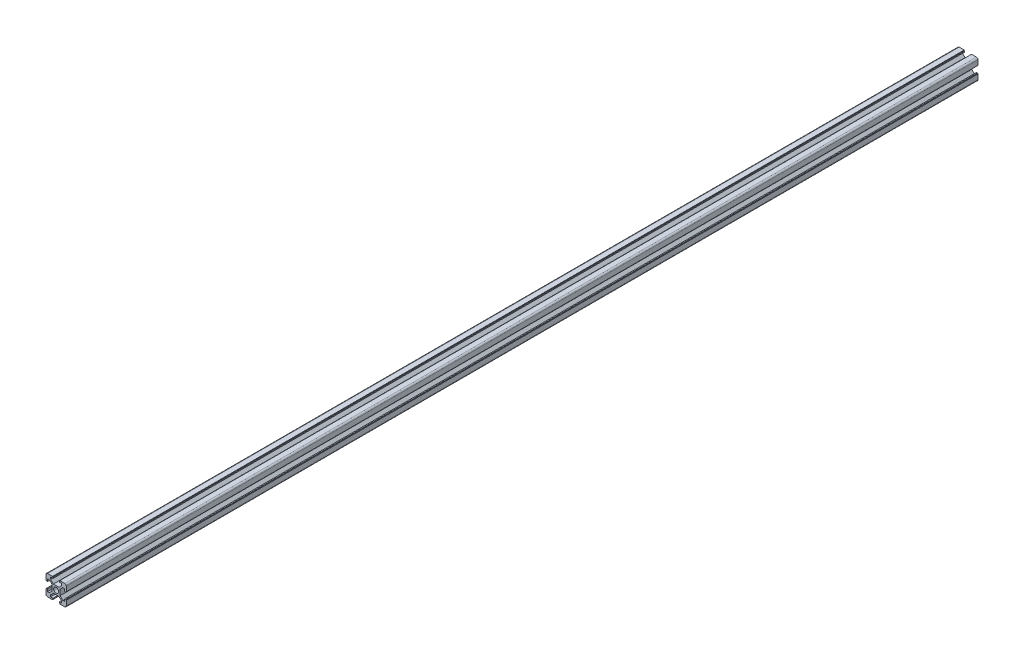
SolidWorks part; units mm, degrees
material "6061 合金"
ref_plane "前视基准面" through (0, 0, 0) normal (0, 0, 1) x (1, 0, 0)
ref_plane "上视基准面" through (0, 0, 0) normal (0, 1, 0) x (1, 0, 0)
ref_plane "右视基准面" through (0, 0, 0) normal (1, 0, 0) x (0, 0, -1)
sketch "草图1" plane through (0, 0, 0) normal (0, 0, 1) x (1, 0, 0)
  line B0 (8.5, 10) -> (3.6, 10)
  line B1 (10, 3.6) -> (10, 8.5)
  line B2 (9.5, 3.6) -> (10, 3.6)
  line B3 (9.5, 3.1) -> (9.5, 3.6)
  line B4 (8.5, 3.1) -> (9.5, 3.1)
  line B5 (8.5, 5.5) -> (8.5, 3.1)
  line B6 (6.65, 5.5) -> (8.5, 5.5)
  line B7 (3.9, 2.75) -> (6.65, 5.5)
  line B8 (3.9, -2.75) -> (3.9, 2.75)
  line B9 (6.65, -5.5) -> (3.9, -2.75)
  line B10 (8.5, -5.5) -> (6.65, -5.5)
  line B11 (8.5, -3.1) -> (8.5, -5.5)
  line B12 (9.5, -3.1) -> (8.5, -3.1)
  line B13 (9.5, -3.6) -> (9.5, -3.1)
  line B14 (10, -3.6) -> (9.5, -3.6)
  line B15 (10, -8.5) -> (10, -3.6)
  line B16 (3.6, -10) -> (8.5, -10)
  line B17 (3.6, -9.5) -> (3.6, -10)
  line B18 (3.1, -9.5) -> (3.6, -9.5)
  line B19 (3.1, -8.5) -> (3.1, -9.5)
  line B20 (5.5, -8.5) -> (3.1, -8.5)
  line B21 (5.5, -6.65) -> (5.5, -8.5)
  line B22 (2.75, -3.9) -> (5.5, -6.65)
  line B23 (-2.75, -3.9) -> (2.75, -3.9)
  line B24 (-5.5, -6.65) -> (-2.75, -3.9)
  line B25 (-5.5, -8.5) -> (-5.5, -6.65)
  line B26 (-3.1, -8.5) -> (-5.5, -8.5)
  line B27 (-3.1, -9.5) -> (-3.1, -8.5)
  line B28 (-3.6, -9.5) -> (-3.1, -9.5)
  line B29 (-3.6, -10) -> (-3.6, -9.5)
  line B30 (-8.5, -10) -> (-3.6, -10)
  line B31 (-10, -3.6) -> (-10, -8.5)
  line B32 (-9.5, -3.6) -> (-10, -3.6)
  line B33 (-9.5, -3.1) -> (-9.5, -3.6)
  line B34 (-8.5, -3.1) -> (-9.5, -3.1)
  line B35 (-8.5, -5.5) -> (-8.5, -3.1)
  line B36 (-6.65, -5.5) -> (-8.5, -5.5)
  line B37 (-3.9, -2.75) -> (-6.65, -5.5)
  line B38 (-3.9, 2.75) -> (-3.9, -2.75)
  line B39 (-6.65, 5.5) -> (-3.9, 2.75)
  line B40 (-8.5, 5.5) -> (-6.65, 5.5)
  line B41 (-8.5, 3.1) -> (-8.5, 5.5)
  line B42 (-9.5, 3.1) -> (-8.5, 3.1)
  line B43 (-9.5, 3.6) -> (-9.5, 3.1)
  line B44 (-10, 3.6) -> (-9.5, 3.6)
  line B45 (-10, 8.5) -> (-10, 3.6)
  line B46 (-3.6, 10) -> (-8.5, 10)
  line B47 (-3.6, 9.5) -> (-3.6, 10)
  line B48 (-3.1, 9.5) -> (-3.6, 9.5)
  line B49 (-3.1, 8.5) -> (-3.1, 9.5)
  line B50 (-5.5, 8.5) -> (-3.1, 8.5)
  line B51 (-5.5, 6.65) -> (-5.5, 8.5)
  line B52 (-2.75, 3.9) -> (-5.5, 6.65)
  line B53 (2.75, 3.9) -> (-2.75, 3.9)
  line B54 (5.5, 6.65) -> (2.75, 3.9)
  line B55 (5.5, 8.5) -> (5.5, 6.65)
  line B56 (3.1, 8.5) -> (5.5, 8.5)
  line B57 (3.1, 9.5) -> (3.1, 8.5)
  line B58 (3.6, 9.5) -> (3.1, 9.5)
  line B59 (3.6, 10) -> (3.6, 9.5)
  arc B60 (-2.5, 0) -> (2.5, 0) centre (0, 0) ccw
  arc B61 (2.5, 0) -> (-2.5, 0) centre (0, 0) ccw
  arc B62 (10, 8.5) -> (8.5, 10) centre (8.5, 8.5) ccw
  arc B63 (8.5, -10) -> (10, -8.5) centre (8.5, -8.5) ccw
  arc B64 (-10, -8.5) -> (-8.5, -10) centre (-8.5, -8.5) ccw
  arc B65 (-8.5, 10) -> (-10, 8.5) centre (-8.5, 8.5) ccw
sketch_block_instance "2020铝型材-1"
sketch_block "2020铝型材"
extrude "凸台-拉伸1" add sketch "草图1" along normal blind 900
sketch "草图5" plane through (0, 3.9, 0) normal (0, 1, 0) x (1, 0, 0)
  line L0 (8.5, -900) -> (8.5, 0) construction
  line L1 (2.75, -900) -> (-2.75, -900) construction
  line L2 (10, -900) -> (10, 0) construction
  circle A4 centre (0, -100) radius 2.1
  circle A5 centre (0, -300) radius 2.1
  circle A6 centre (0, -720) radius 2.1
  circle A7 centre (0, -590) radius 2.1
  dimension "D5" = 180
  dimension "D6" = 4.2
  dimension "D7" = 4.2
  dimension "D8" = 10
  dimension "D9" = 10
  dimension "D10" = 4.2
  dimension "D11" = 10
  dimension "D12" = 4.2
  dimension "D1" = 200
  dimension "D2" = 290
  dimension "D3" = 130
  dimension "D4" = 8.5
sketch "草图6" plane through (0, 3.9, 0) normal (0, 1, 0) x (1, 0, 0)
  line L0 (10, -900) -> (10, 0) construction
  line L1 (8.5, -900) -> (3.6, -900) construction
  line L4 (2.75, 0) -> (-2.75, 0)
  line L5 (-2.75, 0) -> (-2.75, -900)
  line L6 (-2.75, -900) -> (2.75, -900)
  line L7 (2.75, -900) -> (2.75, 0)
  line L8 (2.75, 0) -> (-2.75, 0)
  line L9 (-2.75, 0) -> (-2.75, -900)
  line L10 (-2.75, -900) -> (2.75, -900)
  line L11 (2.75, -900) -> (2.75, 0)
  circle A2 centre (0, -590) radius 2.1
  circle A3 centre (0, -720) radius 2.1
  dimension "D2" = 4.2
  dimension "D3" = 4.2
  dimension "D4" = 310
  dimension "D5" = 10
  dimension "D6" = 10
  dimension "D7" = 180
  dimension "D1" = 0
extrude "切除-拉伸3" cut sketch "草图6" against normal through all contours A2
extrude "切除-拉伸4" cut sketch "草图5" against normal through all contours A6
sketch "草图7" plane through (0, 3.9, 0) normal (0, 1, 0) x (1, 0, 0)
  line L0 (10, -900) -> (10, 0) construction
  line L4 (2.75, 0) -> (-2.75, 0)
  line L5 (-2.75, 0) -> (-2.75, -900)
  line L6 (-2.75, -900) -> (2.75, -900)
  line L7 (2.75, -900) -> (2.75, 0)
  line L8 (2.75, 0) -> (-2.75, 0)
  line L9 (-2.75, 0) -> (-2.75, -900)
  line L10 (-2.75, -900) -> (2.75, -900)
  line L11 (2.75, -900) -> (2.75, 0)
  circle A2 centre (0, -300) radius 2.1
  circle A3 centre (0, -100) radius 2.1
  dimension "D2" = 200
  dimension "D4" = 4.2
  dimension "D5" = 10
  dimension "D6" = 10
  dimension "D7" = 4.2
  dimension "D3" = 100
  dimension "D1" = 0
extrude "切除-拉伸5" cut sketch "草图7" against normal through all contours A3 | A2
